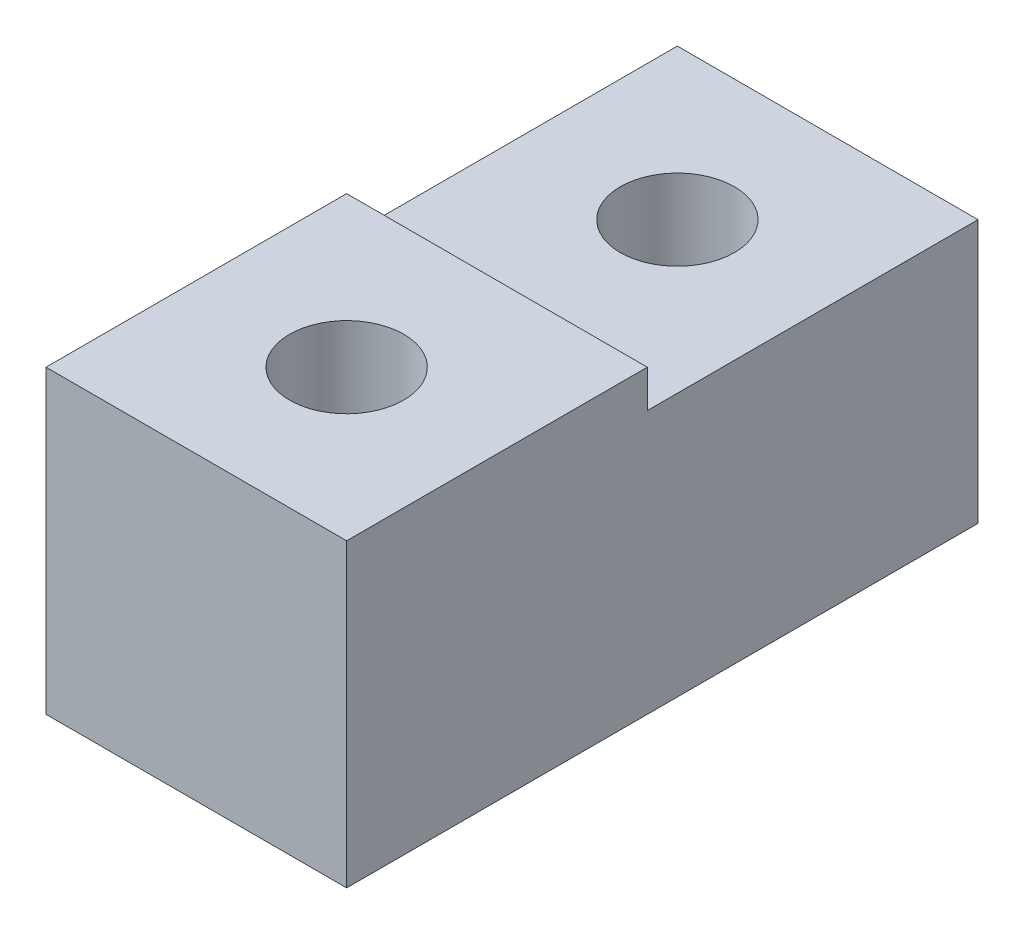
SolidWorks part; units mm, degrees
ref_plane "Front Plane" through (0, 0, 0) normal (0, 0, 1) x (1, 0, 0)
ref_plane "Top Plane" through (0, 0, 0) normal (0, 1, 0) x (1, 0, 0)
ref_plane "Right Plane" through (0, 0, 0) normal (1, 0, 0) x (0, 0, -1)
sketch "Sketch1" plane through (0, 0, 0) normal (0, 1, 0) x (1, 0, 0)
  line L1 (-5, -10.5) -> (5, -10.5)
  line L2 (-5, -10.5) -> (-5, 10.5)
  line L3 (-5, 10.5) -> (5, 10.5)
  line L4 (5, -10.5) -> (5, 10.5)
  line L5 (-5, -10.5) -> (5, 10.5) construction
  line L6 (-5, 10.5) -> (5, -10.5) construction
  point P0 (0, 0)
  dimension "D1" = 10
  dimension "D2" = 21
extrude "Boss-Extrude1" add sketch "Sketch1" along normal blind 10
sketch "Sketch2" plane through (0, 10, 0) normal (0, 1, 0) x (1, 0, 0)
  line L1 (-5, 10.5) -> (5, 10.5)
  line L2 (-5, 10.5) -> (-5, -0.5)
  line L3 (-5, -0.5) -> (5, -0.5)
  line L4 (5, 10.5) -> (5, -0.5)
  line L5 (5, -10.5) -> (5, 10.5) construction
  dimension "D1" = 11
extrude "Cut-Extrude1" cut sketch "Sketch2" against normal blind 1.25
sketch "Sketch3" plane through (0, 0, 0) normal (0, -1, 0) x (1, 0, 0)
  line L0 (-5, 10.5) -> (5, 10.5) construction
  line L1 (5, -10.5) -> (-5, -10.5) construction
  circle A0 centre (0, 5.5) radius 2.5
  circle A1 centre (0, -5.5) radius 2.5
  dimension "D3" = 5
  dimension "D1" = 5
  dimension "D2" = 5
hole_wizard "CBORE for #6 Binding Head Machine Screw1" positions "Sketch6" profile "Sketch5" counterbore size "#6" standard "ANSI Inch" end condition through all
sketch "Sketch6" plane through (0, 0, 0) normal (0, -1, 0) x (-1, 0, 0)
  point P0 (0, -5.5)
sketch "Sketch5" plane through (0, 0, 5.5) normal (1, 0, 0) x (0, 0, -1)
  line L0 (0, 0) -> (0, 10)
  line L1 (0, 10) -> (1.8986, 10)
  line L3 (1.8986, 10) -> (1.8987, 2.2098)
  line L4 (1.8987, 2.2098) -> (3.9687, 2.2098)
  line L5 (3.9687, 2.2098) -> (3.9687, 0)
  line L7 (3.9687, 0) -> (0, 0)
  line L11 (0, -6.35) -> (0, 107.95) construction
  dimension "Thru Hole Dia." = 3.7973
  dimension "Thru Hole Depth" = 10
  dimension "C'Bore Dia." = 7.9375
  dimension "C'Bore Depth" = 2.2098
hole_wizard "CSK for #6 Flat Head Machine Screw (100)1" positions "Sketch7" profile "Sketch8" countersink size "#6" standard "ANSI Inch" end condition through all
sketch "Sketch7" plane through (0, 0, 0) normal (0, -1, 0) x (-1, 0, 0)
  point P0 (0, 5.5)
sketch "Sketch8" plane through (0, 0, -5.5) normal (1, 0, 0) x (0, 0, -1)
  line L0 (0, 0) -> (0, 10)
  line L1 (0, 10) -> (1.8986, 10)
  line L2 (1.8986, 10) -> (1.8986, 1.38)
  line L3 (1.8986, 1.38) -> (3.5433, 0)
  line L5 (3.5433, 0) -> (0, 0)
  line L6 (-1.8986, 1.38) -> (-3.5433, 0) construction
  line L11 (0, -6.35) -> (0, 107.95) construction
  dimension "Thru Hole Dia." = 3.7973
  dimension "Thru Hole Depth" = 10
  dimension "Near C'Sink Dia." = 7.0866
  dimension "Near C'Sink Angle" = 100
